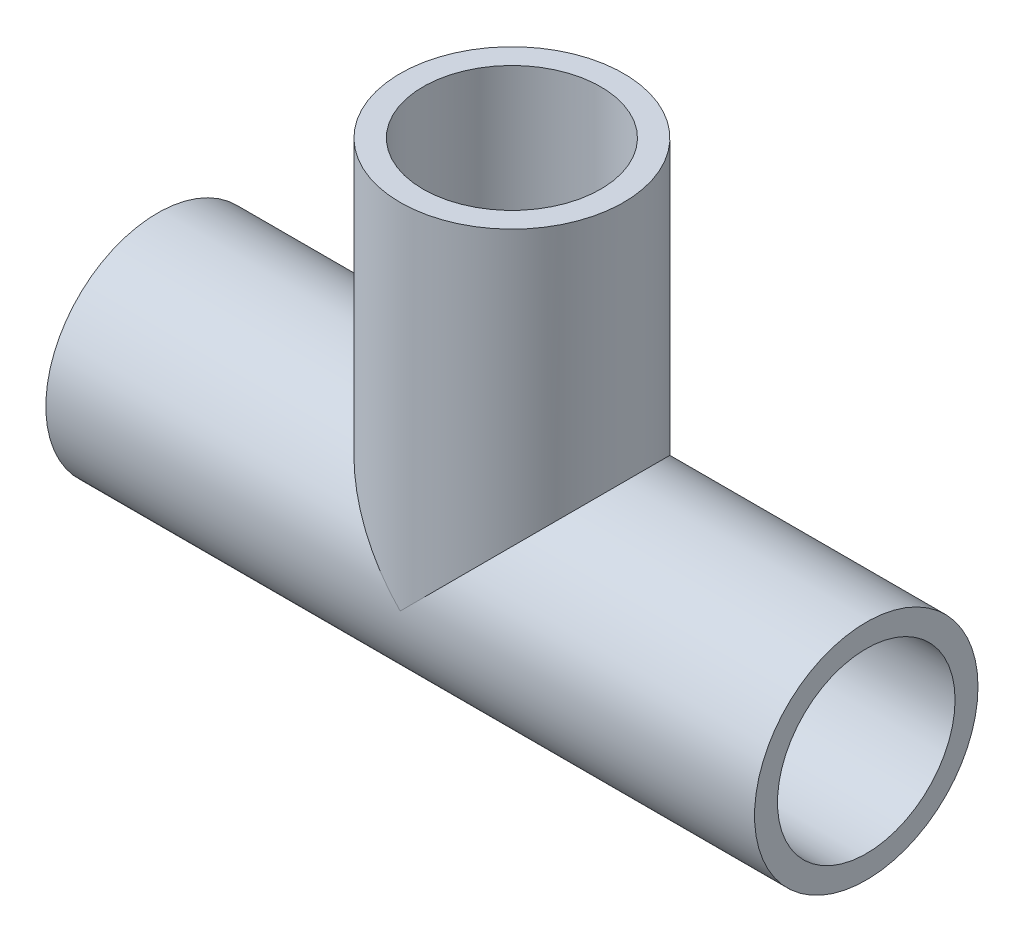
SolidWorks part; units mm, degrees
material "PVC Rígido"
ref_plane "Alzado" through (0, 0, 0) normal (0, 0, 1) x (1, 0, 0)
ref_plane "Planta" through (0, 0, 0) normal (0, 1, 0) x (1, 0, 0)
ref_plane "Vista lateral" through (0, 0, 0) normal (1, 0, 0) x (0, 0, -1)
sketch "Croquis1" plane through (0, 0, 0) normal (1, 0, 0) x (0, 0, -1)
  circle A0 centre (0, 0) radius 10.65
  circle A1 centre (0, 0) radius 13.4
  dimension "D1" = 21.3
  dimension "D2" = 26.8
extrude "Saliente-Extruir1" add sketch "Croquis1" along normal blind 85
sketch "Croquis2" plane through (0, 0, 0) normal (0, 1, 0) x (1, 0, 0)
  line L0 (42.5, 13.4) -> (42.5, -13.4) construction
  line L1 (85, 13.4) -> (0, 13.4) construction
  line L2 (0, -13.4) -> (85, -13.4) construction
  circle A0 centre (42.5, 0) radius 13.4
  circle A1 centre (42.5, 0) radius 10.65
  dimension "D1" = 21.3
extrude "Saliente-Extruir2" add sketch "Croquis2" along normal blind 42.44
sketch "Croquis3" plane through (0, 0, 0) normal (-1, 0, 0) x (0, 0, 1)
  circle A0 centre (0, 0) radius 10.65
  circle A1 centre (0, 0) radius 10.65 construction
extrude "Cortar-Extruir1" cut sketch "Croquis3" against normal blind 84.4974
sketch "Croquis5" plane through (0, 42.44, 0) normal (0, 1, 0) x (1, 0, 0)
  line L0 (31.85, 0) -> (53.15, 0) construction
  circle A0 centre (42.5, 0) radius 10.65 construction
  circle A2 centre (42.5, 0) radius 10.65
  circle A3 centre (42.5, 0) radius 10.65 construction
extrude "Cortar-Extruir2" cut sketch "Croquis5" against normal blind 42.4974
